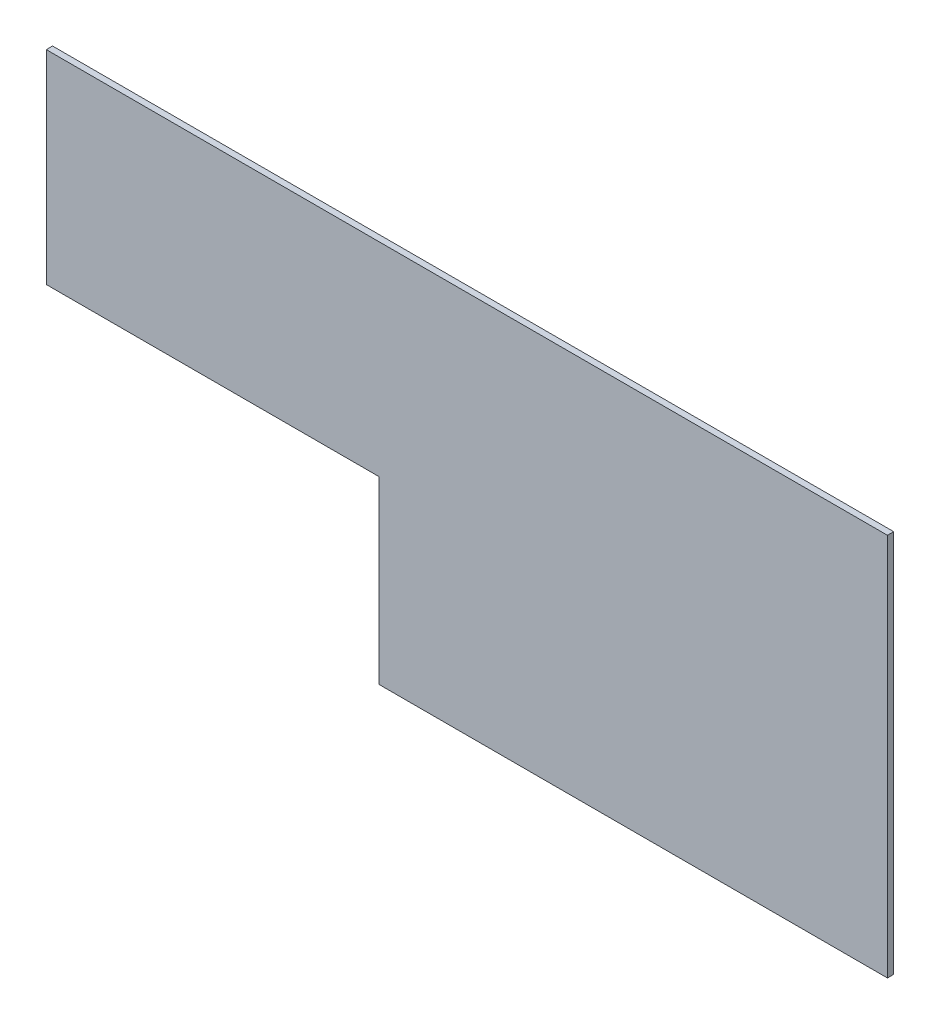
SolidWorks part; units mm, degrees
ref_plane "Front Plane" through (0, 0, 0) normal (0, 0, 1) x (1, 0, 0)
ref_plane "Top Plane" through (0, 0, 0) normal (0, 1, 0) x (1, 0, 0)
ref_plane "Right Plane" through (0, 0, 0) normal (1, 0, 0) x (0, 0, -1)
sketch "Sketch1" plane through (0, 0, 0) normal (0, 0, 1) x (1, 0, 0)
  line L4 (4.3944, 47.7694) -> (89.3944, 47.7694)
  line L5 (89.3944, 47.7694) -> (89.3944, 1.7694)
  line L6 (89.3944, 1.7694) -> (219.3944, 1.7694)
  line L7 (219.3944, 1.7694) -> (219.3944, 99.7694)
  line L8 (219.3944, 99.7694) -> (4.3944, 99.7694)
  line L9 (4.3944, 99.7694) -> (4.3944, 47.7694)
  line L11 (96.1488, 1.7694) -> (121.2557, 1.7694) construction
  dimension "D1" = 215
  dimension "D2" = 98
  dimension "D3" = 46
  dimension "D4" = 85
extrude "Boss-Extrude1" add sketch "Sketch1" along normal blind 1.6
